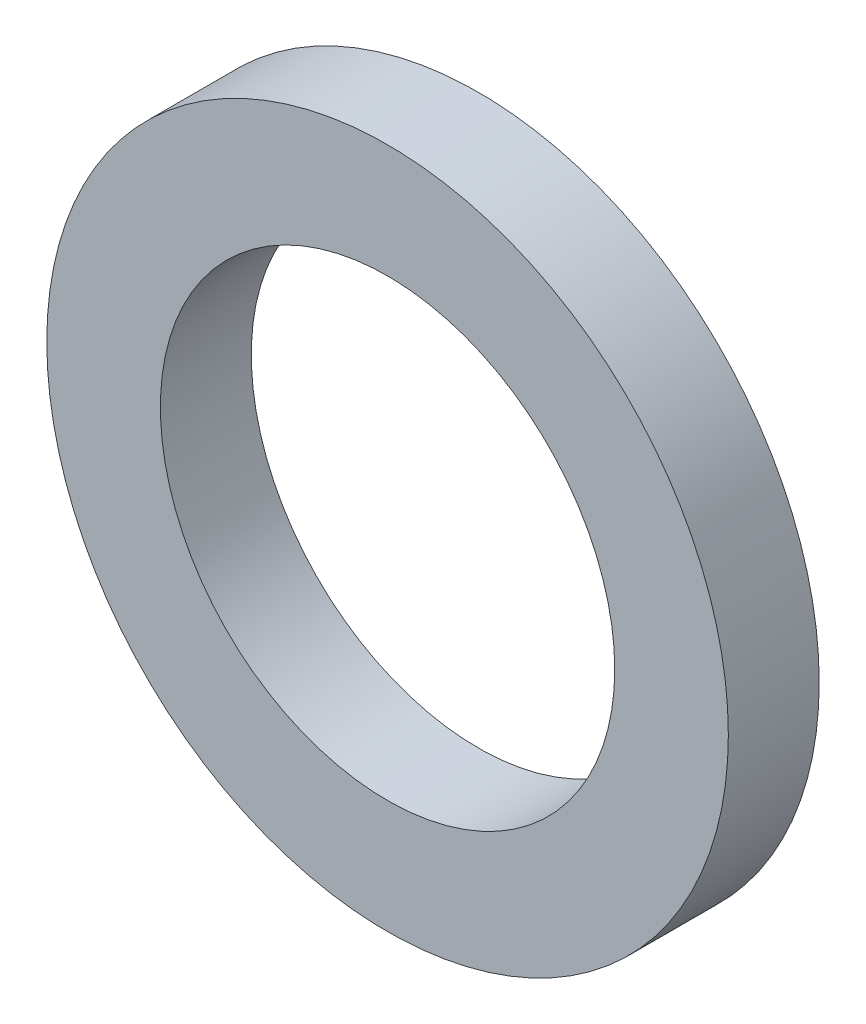
SolidWorks part; units mm, degrees
ref_plane "前视基准面" through (0, 0, 0) normal (0, 0, 1) x (1, 0, 0)
ref_plane "上视基准面" through (0, 0, 0) normal (0, 1, 0) x (1, 0, 0)
ref_plane "右视基准面" through (0, 0, 0) normal (1, 0, 0) x (0, 0, -1)
sketch "草图1" plane through (0, 0, 0) normal (0, 0, 1) x (1, 0, 0)
  circle A0 centre (0, 0) radius 5
  circle A1 centre (0, 0) radius 7.5
  dimension "D1" = 10
  dimension "D2" = 15
extrude "凸台-拉伸1" add sketch "草图1" along normal blind 2
